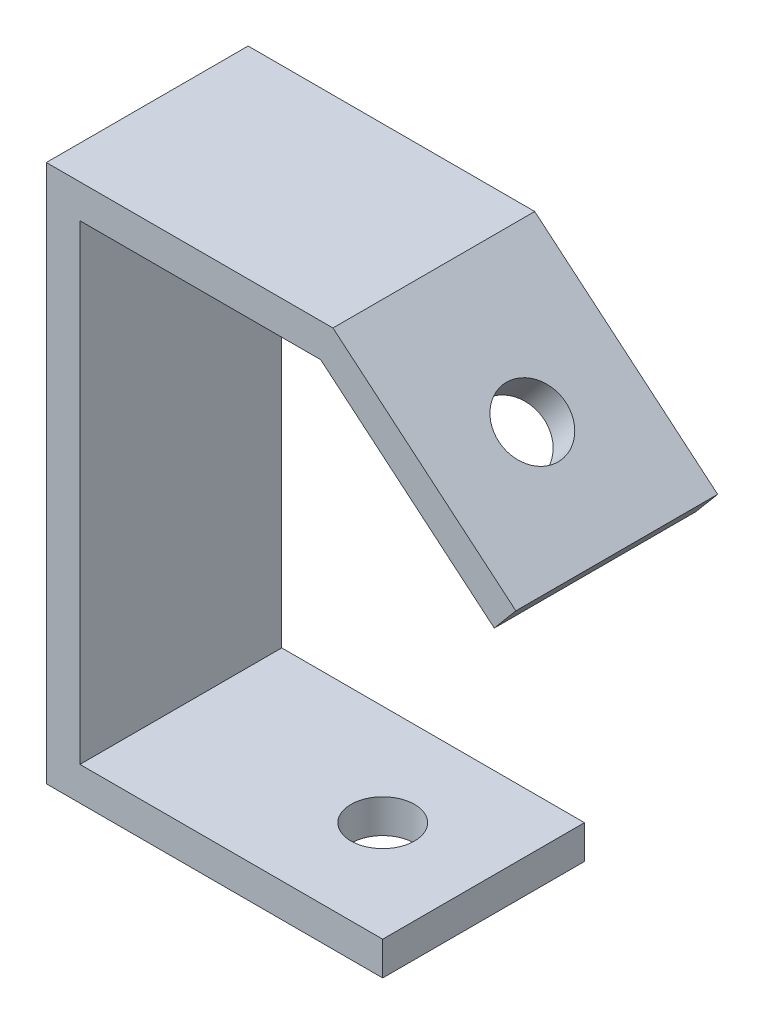
SolidWorks part; units mm, degrees
ref_plane "Front Plane" through (0, 0, 0) normal (0, 0, 1) x (1, 0, 0)
ref_plane "Top Plane" through (0, 0, 0) normal (0, 1, 0) x (1, 0, 0)
ref_plane "Right Plane" through (0, 0, 0) normal (1, 0, 0) x (0, 0, -1)
sketch "Sketch2" plane through (0, 0, 0) normal (0, 0, 1) x (1, 0, 0)
  line L0 (0, -39.7566) -> (63.51, -39.7566)
  line L1 (63.51, -39.7566) -> (63.51, -33.4066)
  line L2 (63.51, -33.4066) -> (6.35, -33.4066)
  line L5 (6.35, -33.4066) -> (6.35, 55.4934)
  line L7 (0, 61.8434) -> (0, -39.7566)
  line L8 (0, 61.8434) -> (54.12, 61.8434)
  line L9 (54.12, 61.8434) -> (88.6609, 32.8601)
  line L11 (6.35, 55.4934) -> (51.8088, 55.4934)
  line L15 (51.8088, 55.4934) -> (84.5792, 27.9957)
  line L17 (0, 55.4934) -> (51.8088, 55.4934) construction
  line L20 (88.6609, 32.8601) -> (84.5792, 27.9957)
  dimension "D1" = 6.35
extrude "Boss-Extrude1" add sketch "Sketch2" along normal blind 38.1
sketch "Sketch3" plane through (0, -39.7566, 0) normal (0, -1, 0) x (1, 0, 0)
  line L0 (63.51, 38.1) -> (63.51, 0) construction
  circle A0 centre (44.47, 19.05) radius 6
  dimension "D1" = 19.04
extrude "Cut-Extrude1" cut sketch "Sketch3" against normal blind 23.1
sketch "Sketch4" plane through (52.813, 62.9401, 0) normal (0.6428, 0.766, 0) x (0.766, -0.6428, 0)
  line L0 (46.7962, -38.1) -> (46.7962, 0) construction
  circle A0 centre (25.9862, -19.05) radius 6.3582
  point P2 (0, 0)
  dimension "D1" = 20.81
extrude "Cut-Extrude2" cut sketch "Sketch4" against normal blind 23.1
